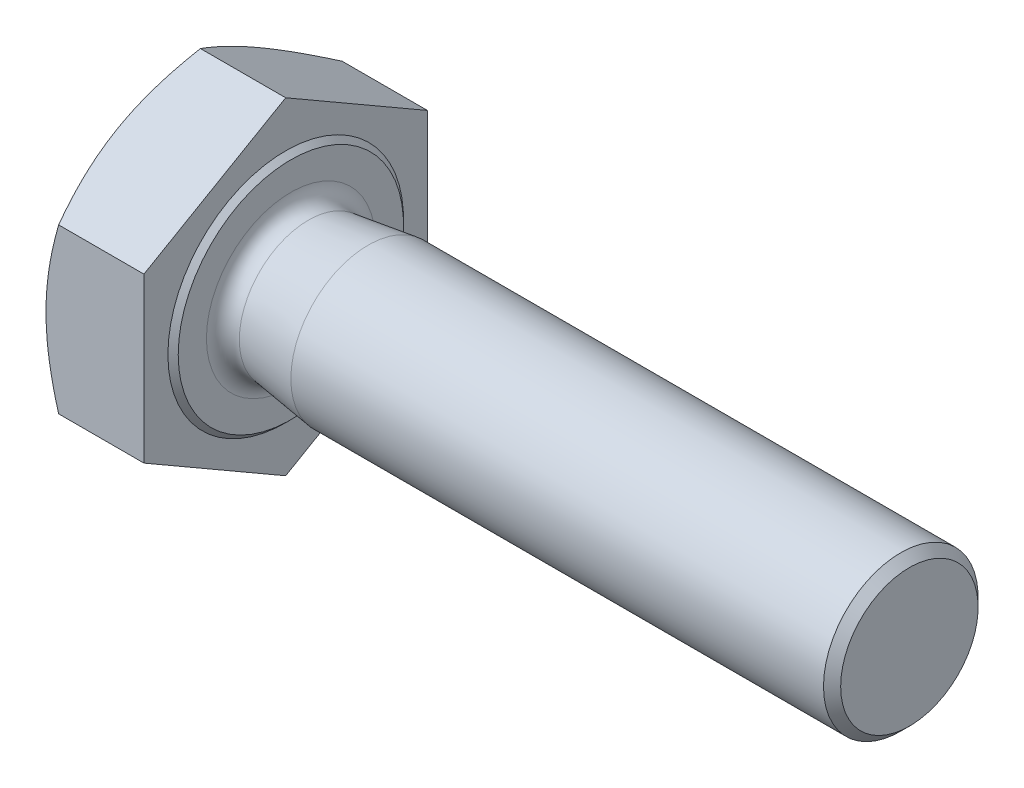
SolidWorks part; units mm, degrees
ref_plane "前视基准面" through (0, 0, 0) normal (0, 0, 1) x (1, 0, 0)
ref_plane "上视基准面" through (0, 0, 0) normal (0, 1, 0) x (1, 0, 0)
ref_plane "右视基准面" through (0, 0, 0) normal (1, 0, 0) x (0, 0, -1)
sketch "草图1" plane through (0, 0, 0) normal (0, 0, 1) x (1, 0, 0)
  line L0 (0, 0) -> (14, 0) construction
  line L1 (0, 0) -> (0, 3.005)
  line L2 (0, 3.005) -> (2, 3.005)
  line L3 (2, 3.005) -> (2, 0)
  line L4 (2, 1.5) -> (14, 1.5)
  line L5 (14, 1.5) -> (14, 0)
  line L6 (0, 2.75) -> (0.1472, 3.005)
  line L7 (13, 1.5) -> (13, 0)
  line L8 (3.5, 1.5) -> (3.5, 0)
  line L9 (2, 1.3376) -> (14, 1.3376)
  line L10 (14, 1.2294) -> (2, 1.2294)
  line L11 (1.9, 2.285) -> (2, 2.185)
  line L12 (1.9, 3.005) -> (1.9, 0)
  line L13 (1.9, 2.285) -> (1.9, 0) construction
  arc A0 (2, 1.8) -> (2.3, 1.5) centre (2.3, 1.8) ccw
  point P12 (13.5, 0)
  point P13 (0.69, 3.005)
  point P14 (2, 1.8)
  point P24 (2, 2.285)
  dimension "D1" = 0.1
  dimension "r" = 0.3
  dimension "k" = 2
  dimension "D2" = 45
  dimension "β" = 30
  dimension "e" = 6.01
  dimension "s" = 5.5
  dimension "d" = 3
  dimension "l" = 12
  dimension "D52" = 1
  dimension "P" = 0.5
  dimension "kw" = 1.31
  dimension "da" = 3.6
  dimension "a" = 1.5
  dimension "ds" = 2.6753
  dimension "D61" = 2.4588
  dimension "dw" = 4.57
  dimension "c" = 0.1
sketch "草图2" plane through (0, 0, 0) normal (1, 0, 0) x (0, 0, -1)
  line L1 (0, 3.1754) -> (-2.75, 1.5877)
  line L2 (-2.75, 1.5877) -> (-2.75, -1.5877)
  line L3 (-2.75, -1.5877) -> (0, -3.1754)
  line L4 (0, -3.1754) -> (2.75, -1.5877)
  line L5 (2.75, -1.5877) -> (2.75, 1.5877)
  line L6 (2.75, 1.5877) -> (0, 3.1754)
  circle A0 centre (0, 0) radius 2.75 construction
sketch "草图3" plane through (0, 0, 0) normal (1, 0, 0) x (0, 0, -1)
  line L0 (2.75, 1.5877) -> (0, 3.1754) construction
  line L1 (0, 3.1754) -> (-2.75, 1.5877) construction
  line L2 (-2.75, 1.5877) -> (-2.75, -1.5877) construction
  line L3 (2.75, -1.5877) -> (2.75, 1.5877) construction
  line L4 (0, -3.1754) -> (2.75, -1.5877) construction
  line L5 (-2.75, -1.5877) -> (0, -3.1754) construction
  line L6 (2.75, 1.5877) -> (0, 3.1754)
  line L7 (0, 3.1754) -> (-2.75, 1.5877)
  line L8 (-2.75, 1.5877) -> (-2.75, -1.5877)
  line L9 (2.75, -1.5877) -> (2.75, 1.5877)
  line L10 (0, -3.1754) -> (2.75, -1.5877)
  line L11 (-2.75, -1.5877) -> (0, -3.1754)
extrude "凸台-拉伸1" add sketch "草图3" along normal up to vertex (2 mm away) up to point (2, 3.005, 0)
sketch "草图4" plane through (0, 0, 0) normal (-1, 0, 0) x (0, 0, 1)
  circle A0 centre (0, 0) radius 2.75 construction
  circle A1 centre (0, 0) radius 2.75
  circle A2 centre (0, 0) radius 6.01
  dimension "D1" = 12.02
extrude "切除-拉伸1" cut sketch "草图4" against normal blind 0.25 draft 60
sketch "草图5" [suppressed] plane through (0, 0, 0) normal (0, 0, 1) x (1, 0, 0)
  line L0 (33, 26) -> (233, 26) construction
  line L1 (233, 26) -> (233, 0) construction
  line L2 (0, 0) -> (233, 0) construction
  line L3 (35.3, 26) -> (233, 26)
  line L4 (233, 26) -> (233, 0)
  line L5 (33, 0) -> (233, 0)
  line L6 (33, 28.3) -> (33, 0)
  arc A0 (33, 28.3) -> (35.3, 26) centre (35.3, 28.3) ccw construction
  arc A1 (33, 28.3) -> (35.3, 26) centre (35.3, 28.3) ccw
revolve "旋转1" [suppressed] add sketch "草图5" angle 360 about L5
cosmetic thread "装饰螺纹线2" [suppressed] parameters "D1"=10.5, "D2"=2.4588
chamfer "倒角2" [suppressed] distance 0.1667 angle 45
sketch "草图7" [suppressed] plane through (0, 0, 0) normal (0, 0, 1) x (1, 0, 0)
  line L0 (33, 37) -> (32, 38)
  line L1 (32, 38) -> (32, 88.25)
  line L2 (32, 88.25) -> (33, 88.25)
  line L3 (33, 88.25) -> (33, 37)
  line L4 (0, 0) -> (233, 0) construction
  line L5 (0, 0) -> (233, 0) construction
  dimension "D1" = 12.02
revolve "切除-旋转1" [suppressed] cut sketch "草图7" angle 360 mid plane about L5
sketch "草图6" plane through (0, 0, 0) normal (0, 0, 1) x (1, 0, 0)
  line L0 (3.5, 0) -> (3.5, 1.5) construction
  line L1 (3.5, 1.5) -> (14, 1.5)
  line L2 (14, 1.5) -> (14, 0)
  line L3 (3.5, 1.5) -> (2.3409, 1.3404)
  line L5 (2, 1.3376) -> (14, 1.3376) construction
  line L6 (2, 3.005) -> (2, 0) construction
  line L7 (2, 1.6376) -> (2, 0)
  line L8 (2, 0) -> (14, 0)
  arc A0 (2.3409, 1.3404) -> (2, 1.6376) centre (2.3, 1.6376) cw
  arc A1 (2, 1.8) -> (2.3, 1.5) centre (2.3, 1.8) ccw construction
revolve "旋转2" add sketch "草图6" angle 360 about L8
cosmetic thread "装饰螺纹线1" parameters "D1"=10.5, "D2"=2.4588
chamfer "倒角1" distance 0.1667 angle 45 1 edges at (14, 0, 1.5)
sketch "草图8" plane through (0, 0, 0) normal (0, 0, 1) x (1, 0, 0)
  line L0 (2, 2.185) -> (1.9, 2.285)
  line L1 (1.9, 2.285) -> (1.9, 6.01)
  line L2 (1.9, 6.01) -> (2, 6.01)
  line L3 (2, 6.01) -> (2, 2.185)
  line L4 (0, 0) -> (14, 0) construction
  line L5 (0, 0) -> (14, 0) construction
  dimension "D1" = 12.02
revolve "切除-旋转2" cut sketch "草图8" angle 360 mid plane about L5
